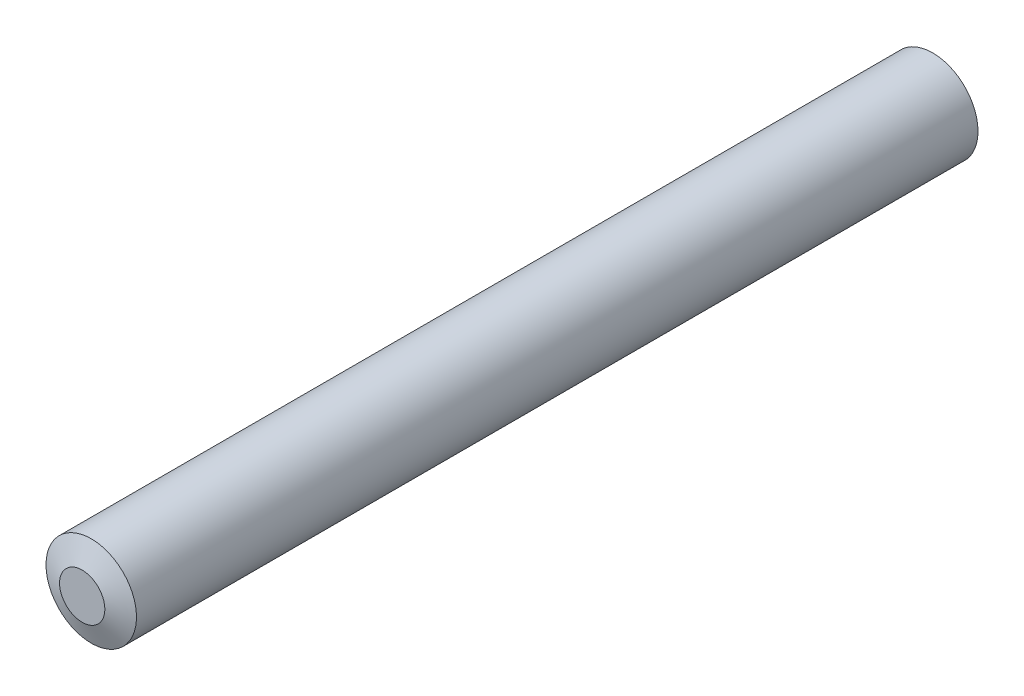
SolidWorks part; units mm, degrees
material "普通碳钢"
ref_plane "前视基准面" through (0, 0, 0) normal (0, 0, 1) x (1, 0, 0)
ref_plane "上视基准面" through (0, 0, 0) normal (0, 1, 0) x (1, 0, 0)
ref_plane "右视基准面" through (0, 0, 0) normal (1, 0, 0) x (0, 0, -1)
sketch "草图1" plane through (0, 0, 0) normal (0, 0, 1) x (1, 0, 0)
  circle A0 centre (0, 0) radius 2
  dimension "D1" = 4
extrude "拉伸1" add sketch "草图1" along normal blind 38
chamfer "倒角1" distance 0.4 distance2 1 1 edges at (2, 0, 38)
chamfer "倒角2" distance 1 distance2 0.4 1 edges at (2, 0, 0)
